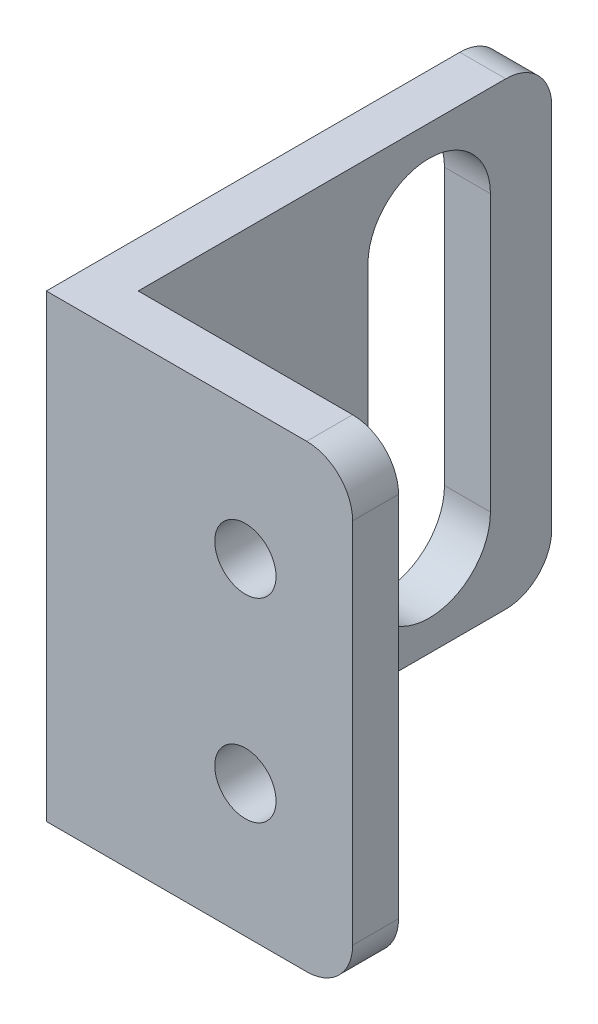
SolidWorks part; units mm, degrees
ref_plane "前视基准面" through (0, 0, 0) normal (0, 0, 1) x (1, 0, 0)
ref_plane "上视基准面" through (0, 0, 0) normal (0, 1, 0) x (1, 0, 0)
ref_plane "右视基准面" through (0, 0, 0) normal (1, 0, 0) x (0, 0, -1)
sketch "草图1" plane through (0, 0, 0) normal (0, 1, 0) x (1, 0, 0)
  line L2 (-1.5, 15) -> (1.5, 15)
  line L3 (-1.5, 15) -> (-1.5, -15)
  line L4 (-1.5, -15) -> (1.5, -15)
  line L5 (1.5, 15) -> (1.5, -15)
  line L6 (-1.5, 15) -> (1.5, -15) construction
  line L7 (-1.5, -15) -> (1.5, 15) construction
  line L8 (-1.5, -15) -> (18.5, -15)
  line L9 (-1.5, -15) -> (-1.5, -12)
  line L10 (-1.5, -12) -> (18.5, -12)
  line L11 (18.5, -15) -> (18.5, -12)
  point P2 (0, 0)
  dimension "D1" = 3
  dimension "D2" = 3
  dimension "D3" = 30
  dimension "D4" = 20
extrude "凸台-拉伸1" add sketch "草图1" along normal blind 30 contours L3 L10 L5 L2 | L10 L3 L4 L5 | L8 L11 L10 L5
sketch "草图2" plane through (0, 0, 15) normal (0, 0, 1) x (1, 0, 0)
  line L0 (11.5, 50) -> (11.5, 0) construction
  line L1 (-1.5, 30) -> (18.5, 30) construction
  line L3 (18.5, 30) -> (18.5, 0) construction
  circle A0 centre (11.5, 21.35) radius 2
  circle A2 centre (11.5, 8.65) radius 2
  circle A3 centre (11.5, -4.05) radius 2
  dimension "D1" = 4
  dimension "D2" = 8.65
  dimension "D4" = 12.7
  dimension "D5" = 7
  dimension "D3" = 3
extrude "切除-拉伸1" cut sketch "草图2" against normal blind 10
sketch "草图3" plane through (-1.5, 0, 0) normal (-1, 0, 0) x (0, 0, 1)
  line L0 (-7, 24) -> (-7, 6) construction
  line L1 (-3, 24) -> (-3, 6)
  line L2 (-11, 24) -> (-11, 6)
  line L4 (-15, 30) -> (-15, 0) construction
  line L5 (-15, 15) -> (15, 15) construction
  line L6 (15, 30) -> (15, 0) construction
  arc A0 (-3, 24) -> (-11, 24) centre (-7, 24) ccw
  arc A1 (-11, 6) -> (-3, 6) centre (-7, 6) ccw
  point P2 (-7, 30)
  point P3 (-7, 15)
  dimension "D3" = 4
  dimension "D1" = 18
  dimension "D2" = 8
extrude "切除-拉伸2" cut sketch "草图3" against normal blind 10
fillet "圆角1" radius 3 4 edges at (0, 0, -15) (0, 30, -15) (18.5, 0, 13.5) (18.5, 30, 13.5)
